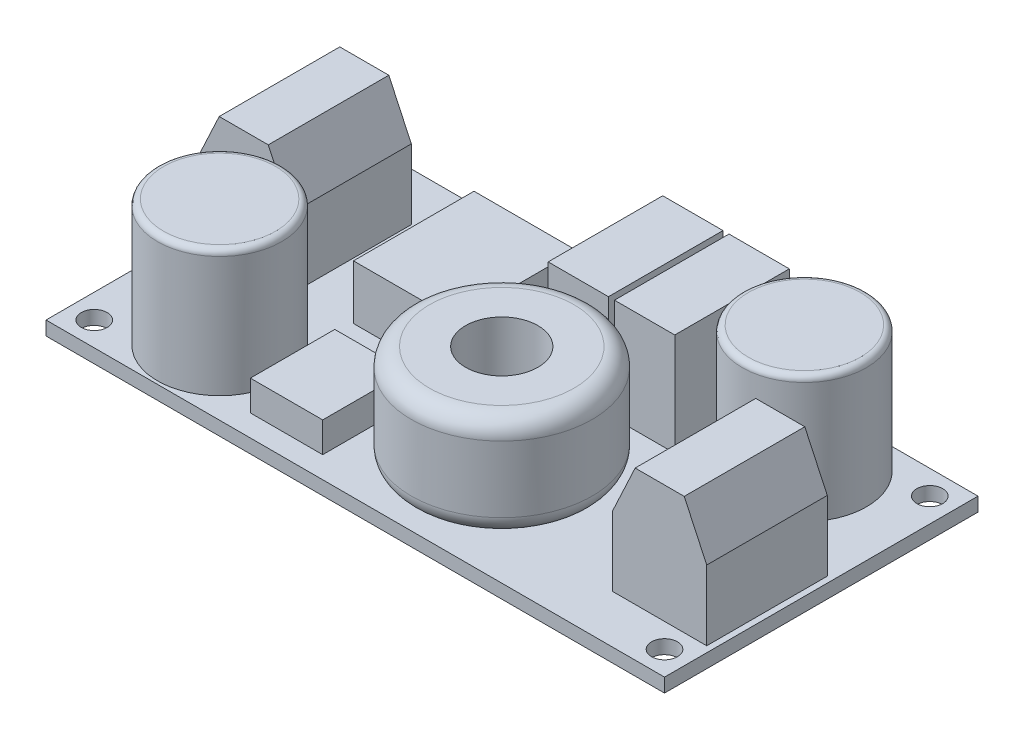
SolidWorks part; units mm, degrees
ref_plane "Alzado" through (0, 0, 0) normal (0, 0, 1) x (1, 0, 0)
ref_plane "Planta" through (0, 0, 0) normal (0, 1, 0) x (1, 0, 0)
ref_plane "Vista lateral" through (0, 0, 0) normal (1, 0, 0) x (0, 0, -1)
sketch "Croquis1" plane through (0, 0, 0) normal (0, 1, 0) x (1, 0, 0)
  line L0 (0, -13) -> (0, 13) construction
  line L1 (-25.65, 13) -> (25.65, 13)
  line L2 (-25.65, 13) -> (-25.65, -13)
  line L3 (-25.65, -13) -> (25.65, -13)
  line L4 (25.65, 13) -> (25.65, -13)
  line L5 (-25.65, 13) -> (25.65, -13) construction
  line L6 (-25.65, -13) -> (25.65, 13) construction
  line L7 (-25.65, 0) -> (25.65, 0) construction
  circle A0 centre (23.65, 11) radius 1.075
  circle A1 centre (23.65, -11) radius 1.075
  circle A2 centre (-23.65, -11) radius 1.075
  circle A3 centre (-23.65, 11) radius 1.075
  point P0 (0, 0)
  point P11 (0, 0)
  point P14 (0, 0)
  dimension "D3" = 2.15
  dimension "D1" = 51.3
  dimension "D2" = 26
  dimension "D4" = 2
  dimension "D5" = 2
extrude "Saliente-Extruir1" add sketch "Croquis1" along normal blind 1.15
sketch "Croquis2" plane through (0, 1.15, 0) normal (0, 1, 0) x (1, 0, 0)
  line L0 (0, -13) -> (0, 13) construction
  line L1 (25.65, 13) -> (-25.65, 13) construction
  line L2 (-25.65, 0) -> (25.65, 0) construction
  line L3 (25.65, -13) -> (25.65, 13) construction
  circle A0 centre (16.65, 7.6) radius 5.15
  circle A1 centre (16.65, -7.6) radius 5.15 construction
  circle A2 centre (-16.65, -7.6) radius 5.15
  point P6 (0, 0)
  point P12 (0, 0)
  point P14 (16.65, 12.75)
  dimension "D1" = 10.3
  dimension "D2" = 9
  dimension "D3" = 0.25
extrude "Saliente-Extruir2" add sketch "Croquis2" along normal blind 10.5 separate body
fillet "Redondeo1" radius 0.5 1 edges at (-16.65, 11.65, 12.75)
fillet "Redondeo2" radius 0.5 1 edges at (16.65, 11.65, -2.45)
sketch "Croquis3" plane through (0, 1.15, 0) normal (0, 1, 0) x (1, 0, 0)
  line L0 (0, -13) -> (0, 13) construction
  line L1 (25.65, 13) -> (-25.65, 13) construction
  line L2 (-25.65, 0) -> (25.65, 0) construction
  line L3 (25.65, -13) -> (25.65, 13) construction
  line L4 (-25.65, -13) -> (25.65, -13) construction
  line L5 (17.35, 1) -> (25.15, 1)
  line L6 (17.35, 1) -> (17.35, -9)
  line L7 (17.35, -9) -> (25.15, -9)
  line L8 (25.15, 1) -> (25.15, -9)
  line L9 (-17.35, -9) -> (-25.15, -9) construction
  line L10 (-25.15, 1) -> (-25.15, -9) construction
  line L11 (-17.35, 1) -> (-25.15, 1) construction
  line L12 (-17.35, 1) -> (-17.35, -9) construction
  line L13 (-17.35, 9) -> (-25.15, 9)
  line L14 (-17.35, -1) -> (-17.35, 9)
  line L15 (-17.35, -1) -> (-25.15, -1)
  line L16 (-25.15, -1) -> (-25.15, 9)
  point P6 (0, 0)
  point P12 (0, 0)
  dimension "D1" = 10
  dimension "D2" = 7.8
  dimension "D3" = 4
  dimension "D4" = 0.5
extrude "Saliente-Extruir3" add sketch "Croquis3" along normal blind 9.8 separate body
chamfer "Chaflán1" distance 4 angle 25 2 edges at (17.35, 10.95, 4) (25.15, 10.95, 4)
chamfer "Chaflán2" distance 4 angle 25 2 edges at (-25.15, 10.95, -4) (-17.35, 10.95, -4)
sketch "Croquis5" plane through (0, 1.15, 0) normal (0, 1, 0) x (1, 0, 0)
  line L0 (25.65, 13) -> (-25.65, 13) construction
  line L1 (5, 13) -> (10, 13)
  line L2 (5, 13) -> (5, 3.5)
  line L3 (5, 3.5) -> (10, 3.5)
  line L4 (10, 13) -> (10, 3.5)
  line L5 (-0.5, 13) -> (4.5, 13)
  line L6 (-0.5, 13) -> (-0.5, 3.5)
  line L7 (-0.5, 3.5) -> (4.5, 3.5)
  line L8 (4.5, 13) -> (4.5, 3.5)
  circle A0 centre (16.65, 7.6) radius 5.15 construction
  circle A1 centre (16.65, 7.6) radius 4.65 construction
  circle A2 centre (16.65, 7.6) radius 4.65 construction
  point P8 (11.5, 7.6)
  dimension "D1" = 5
  dimension "D2" = 9.5
  dimension "D3" = 1.5
  dimension "D4" = 0.5
extrude "Saliente-Extruir4" add sketch "Croquis5" along normal blind 8.5 separate body
sketch "Croquis6" plane through (0, 1.15, 0) normal (0, 1, 0) x (1, 0, 0)
  line L0 (-25.65, 13) -> (-25.65, -13) construction
  line L1 (-12.65, 9.5) -> (-4.15, 9.5)
  line L2 (-12.65, 9.5) -> (-12.65, -0.5)
  line L3 (-12.65, -0.5) -> (-4.15, -0.5)
  line L4 (-4.15, 9.5) -> (-4.15, -0.5)
  line L5 (25.65, 13) -> (-25.65, 13) construction
  dimension "D1" = 10
  dimension "D2" = 8.5
  dimension "D3" = 13
  dimension "D4" = 3.5
extrude "Saliente-Extruir5" add sketch "Croquis6" along normal blind 4.5 separate body
sketch "Croquis7" plane through (0, 1.15, 0) normal (0, 1, 0) x (1, 0, 0)
  line L0 (-25.65, -13) -> (25.65, -13) construction
  line L1 (-10.5, -4.2) -> (-4.5, -4.2)
  line L2 (-10.5, -4.2) -> (-10.5, -11.2)
  line L3 (-10.5, -11.2) -> (-4.5, -11.2)
  line L4 (-4.5, -4.2) -> (-4.5, -11.2)
  circle A0 centre (-16.65, -7.6) radius 4.65 construction
  circle A1 centre (-16.65, -7.6) radius 4.65 construction
  circle A2 centre (-16.65, -7.6) radius 5.15 construction
  point P7 (-11.5, -7.6)
  dimension "D1" = 6
  dimension "D2" = 1
  dimension "D3" = 7
  dimension "D4" = 1.8
extrude "Saliente-Extruir6" add sketch "Croquis7" along normal blind 2.5 separate body
ref_plane "Plano1" through (3.65, 0, 0) normal (1, 0, 0) x (0, 0, -1)
sketch "Croquis8" plane through (3.65, 0, 0) normal (1, 0, 0) x (0, 0, -1)
  line L0 (-13, 1.15) -> (13, 1.15) construction
  line L1 (-12, 9.65) -> (-7.5, 9.65)
  line L2 (-12, 9.65) -> (-12, 1.15)
  line L3 (-12, 1.15) -> (-7.5, 1.15)
  line L4 (-7.5, 9.65) -> (-7.5, 1.15)
  line L5 (-13, 1.15) -> (-13, 0) construction
  line L6 (-4.5, 1.15) -> (-4.5, 9.65) construction
  dimension "D1" = 8.5
  dimension "D2" = 4.5
  dimension "D3" = 1
  dimension "D4" = 15
revolve "Revolución1" add sketch "Croquis8" angle 360 about L6
fillet "Redondeo3" radius 1.5 2 edges at (3.65, 1.15, -3) (3.65, 9.65, -3)
